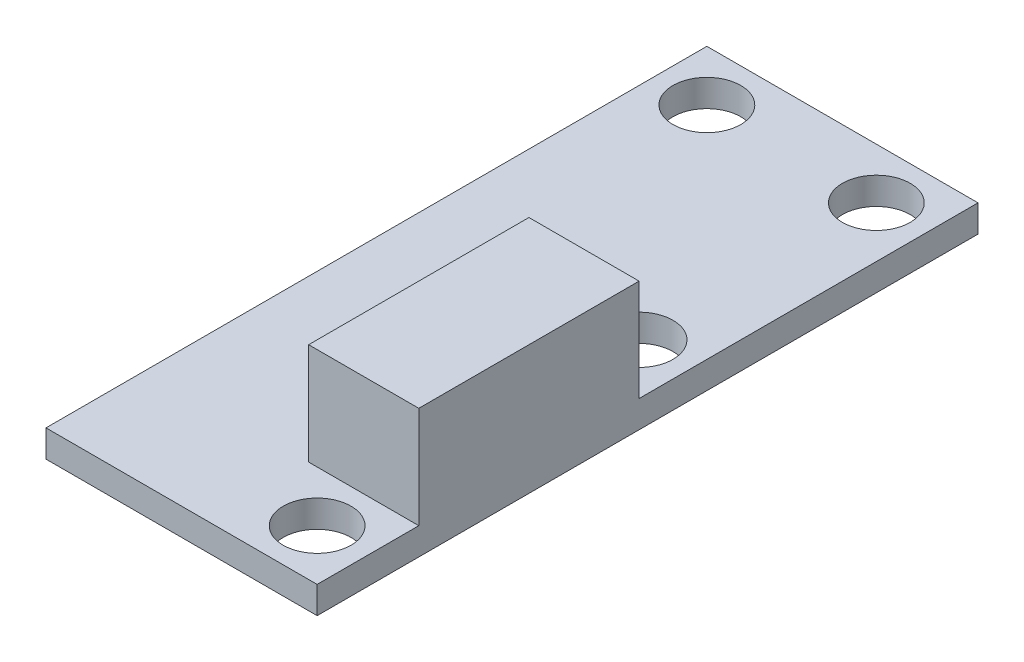
SolidWorks part; units mm, degrees
ref_plane "Plan de face" through (0, 0, 0) normal (0, 0, 1) x (1, 0, 0)
ref_plane "Plan de dessus" through (0, 0, 0) normal (0, 1, 0) x (1, 0, 0)
ref_plane "Plan de droite" through (0, 0, 0) normal (1, 0, 0) x (0, 0, -1)
sketch "Sketch1" plane through (0, 0, 0) normal (0, 1, 0) x (1, 0, 0)
  line L0 (5, 2.5) -> (5, -19.5) construction
  line L1 (8, 19.5) -> (-8, 19.5)
  line L2 (8, 19.5) -> (8, -19.5)
  line L3 (8, -19.5) -> (-8, -19.5)
  line L4 (-8, 19.5) -> (-8, -19.5)
  line L5 (8, 19.5) -> (-8, -19.5) construction
  line L6 (8, -19.5) -> (-8, 19.5) construction
  circle A0 centre (5, -16.5) radius 2
  circle A1 centre (5, 2.5) radius 2
  circle A2 centre (5, 16.5) radius 2
  circle A3 centre (-5, 16.5) radius 2
  point P0 (0, 0)
  dimension "D3" = 4
  dimension "D6" = 4
  dimension "D9" = 4
  dimension "D12" = 4
  dimension "D1" = 16
  dimension "D2" = 39
  dimension "D4" = 3
  dimension "D5" = 3
  dimension "D7" = 3
  dimension "D8" = 22
  dimension "D10" = 3
  dimension "D11" = 3
  dimension "D13" = 3
  dimension "D14" = 3
extrude "Boss-Extrude1" add sketch "Sketch1" along normal mid plane 1.6
sketch "Sketch2" plane through (0, 0.8, 0) normal (0, 1, 0) x (1, 0, 0)
  line L0 (8, -19.5) -> (8, 19.5) construction
  line L1 (8, -0.5) -> (1.5, -0.5)
  line L2 (8, -0.5) -> (8, -13.5)
  line L3 (8, -13.5) -> (1.5, -13.5)
  line L4 (1.5, -0.5) -> (1.5, -13.5)
  line L5 (-8, -19.5) -> (8, -19.5) construction
  dimension "D1" = 13
  dimension "D2" = 6
  dimension "D3" = 6.5
extrude "Boss-Extrude2" add sketch "Sketch2" along normal blind 6
sketch "Sketch3" plane through (0, 0.8, 0) normal (0, 1, 0) x (1, 0, 0)
  line L0 (-8, 19.5) -> (-8, -19.5) construction
  line L1 (-8, 19.5) -> (-13, 19.5)
  line L2 (-8, 19.5) -> (-8, -19.5)
  line L3 (-8, -19.5) -> (-13, -19.5)
  line L4 (-13, 19.5) -> (-13, -19.5)
  line L5 (-8, -19.5) -> (8, -19.5)
  line L6 (8, -19.5) -> (8, 19.5)
  line L7 (8, 19.5) -> (-8, 19.5)
  circle A0 centre (5, 2.5) radius 2
  circle A1 centre (5, -16.5) radius 2
  dimension "D1" = 5
